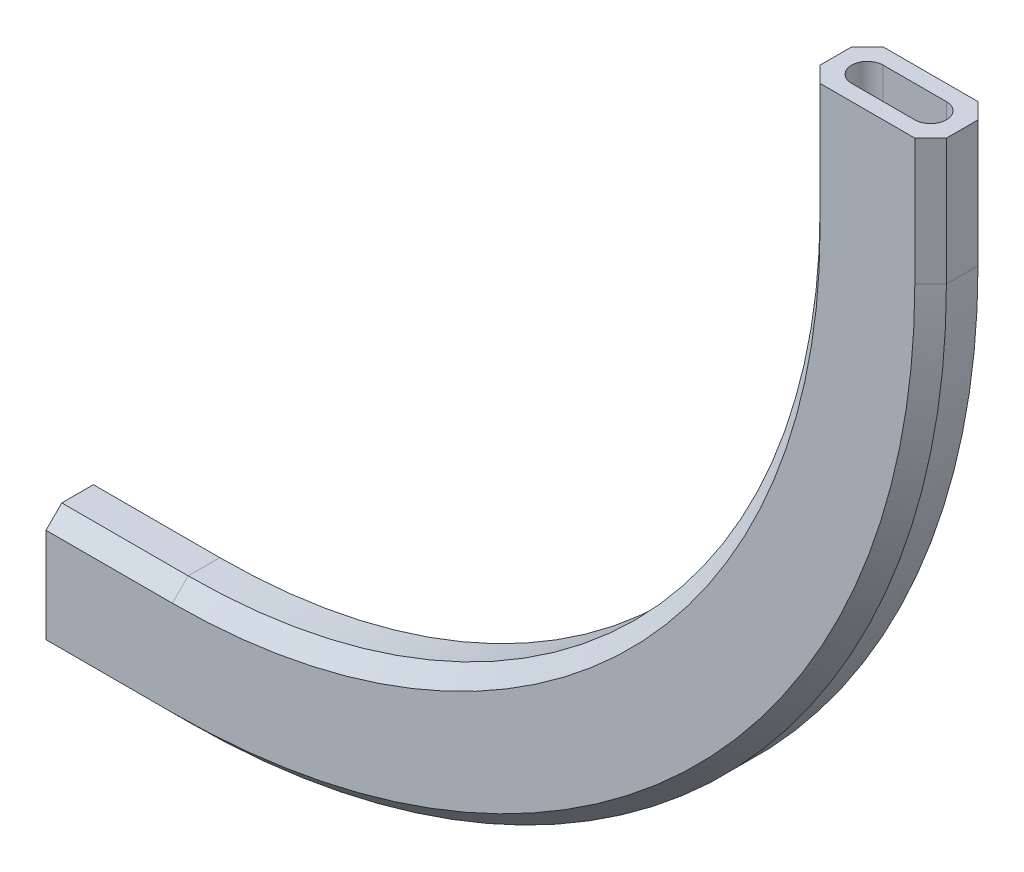
SolidWorks part; units mm, degrees
material "6061-T6 (SS)"
ref_plane "Front Plane" through (0, 0, 0) normal (0, 0, 1) x (1, 0, 0)
ref_plane "Top Plane" through (0, 0, 0) normal (0, 1, 0) x (1, 0, 0)
ref_plane "Right Plane" through (0, 0, 0) normal (1, 0, 0) x (0, 0, -1)
sketch "Sketch1" plane through (0, 0, 0) normal (0, 0, 1) x (1, 0, 0)
  line L0 (0, 0) -> (12.7, 0)
  line L1 (76.2, 63.5) -> (76.2, 76.2)
  line L2 (0, -12.7) -> (12.7, -12.7)
  line L3 (88.9, 63.5) -> (88.9, 76.2)
  line L4 (0, 0) -> (0, -12.7)
  line L5 (76.2, 76.2) -> (88.9, 76.2)
  arc A0 (76.2, 63.5) -> (12.7, 0) centre (12.7, 63.5) cw
  arc A1 (88.9, 63.5) -> (12.7, -12.7) centre (12.7, 63.5) cw
  point P6 (76.2, 0)
  dimension "D3" = 63.5
  dimension "D1" = 76.2
  dimension "D2" = 76.2
  dimension "D4" = 12.7
extrude "Boss-Extrude1" add sketch "Sketch1" along normal blind 6.35
sketch "Sketch2" plane through (0, 76.2, 0) normal (0, 1, 0) x (1, 0, 0)
  line L0 (82.55, 0) -> (82.55, -6.35) construction
  line L1 (88.9, 0) -> (76.2, 0) construction
  line L2 (88.9, -6.35) -> (76.2, -6.35) construction
  line L3 (76.2, -3.175) -> (88.9, -3.175) construction
  line L4 (76.2, -6.35) -> (76.2, 0) construction
  line L5 (88.9, -6.35) -> (88.9, 0) construction
  line L6 (79.375, -3.175) -> (85.725, -3.175) construction
  line L7 (79.375, -1.5875) -> (85.725, -1.5875)
  line L8 (79.375, -4.7625) -> (85.725, -4.7625)
  arc A0 (79.375, -1.5875) -> (79.375, -4.7625) centre (79.375, -3.175) ccw
  arc A1 (85.725, -4.7625) -> (85.725, -1.5875) centre (85.725, -3.175) ccw
  point P14 (82.55, -3.175)
  dimension "D1" = 3.175
extrude "Cut-Extrude2" cut sketch "Sketch2" against normal blind 12.7
sketch "Sketch4" plane through (0, 0, 0) normal (-1, 0, 0) x (0, 0, 1)
  line L0 (3.175, 0) -> (3.175, -12.7) construction
  line L1 (6.35, 0) -> (0, 0) construction
  line L2 (6.35, -12.7) -> (0, -12.7) construction
  line L3 (3.175, -3.175) -> (3.175, -9.525) construction
  line L4 (0, 0) -> (0, -12.7) construction
  line L5 (0, -6.35) -> (6.35, -6.35) construction
  line L6 (6.35, 0) -> (6.35, -12.7) construction
  line L7 (4.7625, -3.175) -> (4.7625, -9.525)
  line L8 (1.5875, -3.175) -> (1.5875, -9.525)
  arc A0 (4.7625, -3.175) -> (1.5875, -3.175) centre (3.175, -3.175) ccw
  arc A1 (1.5875, -9.525) -> (4.7625, -9.525) centre (3.175, -9.525) ccw
  point P14 (3.175, -6.35)
extrude "Cut-Extrude3" cut sketch "Sketch4" against normal blind 12.7
chamfer "Chamfer2" distance 1.5875 angle 45 12 edges at (6.35, -12.7, 0) (88.9, 69.85, 0) (66.5815, 9.6185, 0) (6.35, -12.7, 6.35) (88.9, 69.85, 6.35) (66.5815, 9.6185, 6.35) (76.2, 69.85, 0) (6.35, 0, 0) (57.6013, 18.5987, 0) (76.2, 69.85, 6.35) (6.35, 0, 6.35) (57.6013, 18.5987, 6.35)
